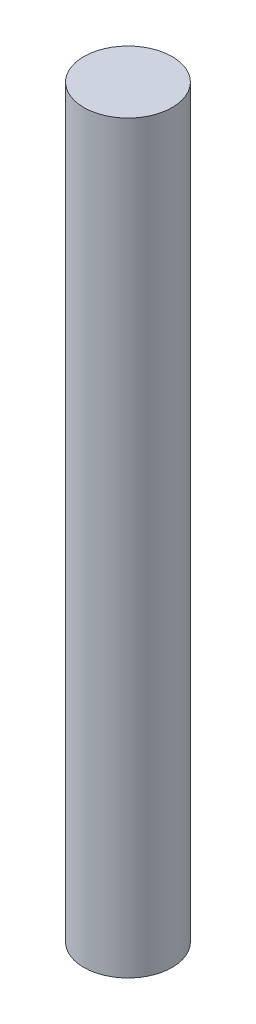
SolidWorks part; units mm, degrees
ref_plane "Front Plane" through (0, 0, 0) normal (0, 0, 1) x (1, 0, 0)
ref_plane "Top Plane" through (0, 0, 0) normal (0, 1, 0) x (1, 0, 0)
ref_plane "Right Plane" through (0, 0, 0) normal (1, 0, 0) x (0, 0, -1)
sketch "Sketch1" plane through (0, 0, 0) normal (0, 1, 0) x (1, 0, 0)
  circle A0 centre (0, 0) radius 3
extrude "Boss-Extrude1" add sketch "Sketch1" along normal blind 50.6
